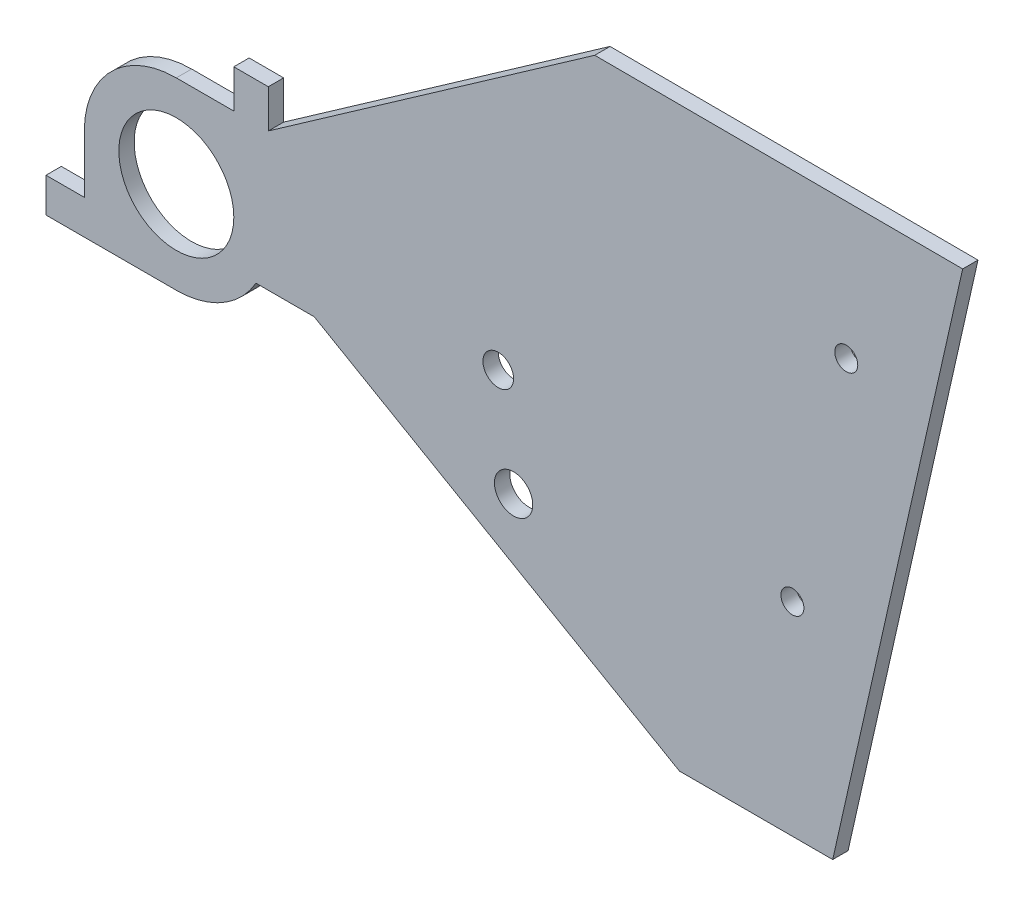
SolidWorks part; units mm, degrees
ref_plane "前视基准面" through (0, 0, 0) normal (0, 0, 1) x (1, 0, 0)
ref_plane "上视基准面" through (0, 0, 0) normal (0, 1, 0) x (1, 0, 0)
ref_plane "右视基准面" through (0, 0, 0) normal (1, 0, 0) x (0, 0, -1)
sketch "草图2" plane through (0, 0, 0) normal (0, 0, 1) x (1, 0, 0)
  line L39 (27, -3) -> (27, 2)
  line L40 (25.3923, -21) -> (33, -21)
  line L41 (22.5, 2) -> (22.5, -3)
  line L42 (22.5, -3) -> (15, -3)
  line L44 (3, -22.5) -> (3, -15)
  line L45 (-2, -22.5) -> (3, -22.5)
  line L46 (-2, -27) -> (15, -27)
  line L47 (27, 2) -> (22.5, 2)
  line L48 (-2, -27) -> (-2, -22.5)
  line L50 (57, -15) -> (59, -28) construction
  line L56 (80.6314, -48.5) -> (100.6314, -48.5)
  line L60 (117.5841, 26.707) -> (100.6314, -48.5)
  line L63 (69.5841, 26.8429) -> (117.5841, 26.707)
  line L64 (27, -3) -> (69.5841, 26.8429)
  line L66 (33, -21) -> (80.6314, -48.5)
  circle A0 centre (57, -15) radius 2
  circle A8 centre (15, -15) radius 7.5
  arc A9 (25.3923, -21) -> (15, -27) centre (15, -15) cw
  arc A14 (15, -3) -> (3, -15) centre (15, -15) ccw
  circle A16 centre (59, -28) radius 2.5
  circle A19 centre (102.3987, 8.9999) radius 1.5
  circle A20 centre (95.3735, -21.9837) radius 1.5
  point P29 (0, -3)
  dimension "D6" = 4
  dimension "D7" = 48
  dimension "D16" = 17.75
  dimension "D8" = 12
  dimension "D27" = 15
  dimension "D34" = 5
  dimension "D5" = 12
  dimension "D4" = 55
  dimension "D23" = 15
  dimension "D35" = 2
  dimension "D9" = 42
  dimension "D10" = 20
  dimension "D19" = 0
  dimension "D13" = 10.92
  dimension "D14" = 10.96
  dimension "D18" = 31.77
  dimension "D11" = 52
  dimension "D15" = 7.5
  dimension "D22" = 4.5
  dimension "D25" = 15
  dimension "D26" = 18
  dimension "D29" = 5
  dimension "D30" = 5
  dimension "D32" = 4.5
  dimension "D36" = 13
extrude "凸台-拉伸1" add sketch "草图2" along normal blind 2 from offset 25
